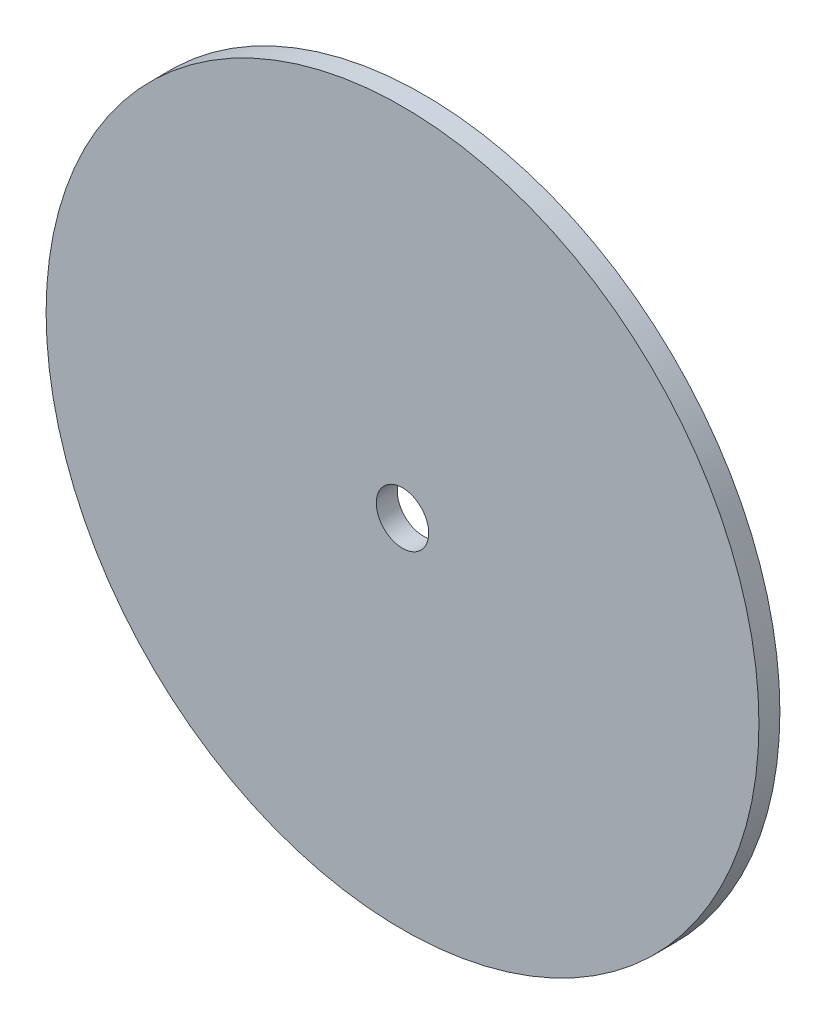
SolidWorks part; units mm, degrees
ref_plane "Front" through (0, 0, 0) normal (0, 0, 1) x (1, 0, 0)
ref_plane "Top" through (0, 0, 0) normal (0, 1, 0) x (1, 0, 0)
ref_plane "Right" through (0, 0, 0) normal (1, 0, 0) x (0, 0, -1)
sketch "Эскиз1" plane through (0, 0, 0) normal (0, 0, 1) x (1, 0, 0)
  circle A0 centre (0, 0) radius 3.4
  dimension "D1" = 6.8
extrude "Бобышка-Вытянуть1" add sketch "Эскиз1" along normal blind 0.2
sketch "Эскиз2" plane through (0, 0, 0) normal (1, 0, 0) x (0, 0, -1)
  line L0 (-4.9825, 0) -> (3.5483, 0) construction
  line L1 (0, 1) -> (-0.0926, 1)
  line L2 (0, -3.4) -> (0, 3.4) construction
  line L3 (-0.0926, 1) -> (-0.0926, 1.1)
  line L4 (-0.0926, 1.1) -> (0, 1.1)
  line L5 (0, 1.1) -> (0, 1)
  line L6 (0, 1.25) -> (-0.0926, 1.25)
  line L7 (-0.0926, 1.25) -> (-0.0926, 1.35)
  line L8 (-0.0926, 1.35) -> (0, 1.35)
  line L9 (0, 1.35) -> (0, 1.25)
  line L10 (0, 1.5) -> (-0.0926, 1.5)
  line L11 (-0.0926, 1.5) -> (-0.0926, 1.6)
  line L12 (-0.0926, 1.6) -> (0, 1.6)
  line L13 (0, 1.6) -> (0, 1.5)
  line L14 (0, 1.75) -> (-0.0926, 1.75)
  line L15 (-0.0926, 1.75) -> (-0.0926, 1.85)
  line L16 (-0.0926, 1.85) -> (0, 1.85)
  line L17 (0, 1.85) -> (0, 1.75)
  line L18 (0, 2) -> (-0.0926, 2)
  line L19 (-0.0926, 2) -> (-0.0926, 2.1)
  line L20 (-0.0926, 2.1) -> (0, 2.1)
  line L21 (0, 2.1) -> (0, 2)
  line L22 (0, 2.25) -> (-0.0926, 2.25)
  line L23 (-0.0926, 2.25) -> (-0.0926, 2.35)
  line L24 (-0.0926, 2.35) -> (0, 2.35)
  line L25 (0, 2.35) -> (0, 2.25)
  line L26 (0, 2.5) -> (-0.0926, 2.5)
  line L27 (-0.0926, 2.5) -> (-0.0926, 2.6)
  line L28 (-0.0926, 2.6) -> (0, 2.6)
  line L29 (0, 2.6) -> (0, 2.5)
  line L30 (0, 2.75) -> (-0.0926, 2.75)
  line L31 (-0.0926, 2.75) -> (-0.0926, 2.85)
  line L32 (-0.0926, 2.85) -> (0, 2.85)
  line L33 (0, 2.85) -> (0, 2.75)
  line L34 (0, 3) -> (-0.0926, 3)
  line L35 (-0.0926, 3) -> (-0.0926, 3.1)
  line L36 (-0.0926, 3.1) -> (0, 3.1)
  line L37 (0, 3.1) -> (0, 3)
  line L38 (0, 3.25) -> (-0.0926, 3.25)
  line L39 (-0.0926, 3.25) -> (-0.0926, 3.35)
  line L40 (-0.0926, 3.35) -> (0, 3.35)
  line L41 (0, 3.35) -> (0, 3.25)
  dimension "D2" = 0.1
  dimension "D3" = 0.15
  dimension "D4" = 1
  dimension "D1" = 10
revolve "Вырез-Повернуть1" cut sketch "Эскиз2" angle 360 about L0
sketch "Эскиз3" plane through (0, 0, 0) normal (0, 0, -1) x (-1, 0, 0)
  line L0 (-3.4, 0) -> (3.35, 0) construction
  line L1 (0, 3.7394) -> (0, -3.8002) construction
  line L2 (-3.5, 2.4) -> (3.5, 2.4) construction
  line L3 (-3.5, -2.7) -> (3.5, -2.7) construction
  circle A0 centre (0, 0) radius 3.4 construction
  circle A1 centre (0, 0) radius 3.35 construction
  text T0 "  45                       15" font "Century Gothic" height 0.5
  text T1 "10" font "Century Gothic" height 0.5
  text T2 "30" font "Century Gothic" height 0.5
  point P16 (0, 2.4)
  point P17 (0, -2.7)
  dimension "D1" = 2.4
  dimension "D2" = 2.7
  dimension "D3" = 7
extrude "Бобышка-Вытянуть2" add sketch "Эскиз3" along normal blind 0.1
sketch "Эскиз4" plane through (0, 0, 0) normal (0, 0, -1) x (-1, 0, 0)
  circle A0 centre (0, 0) radius 0.25
  dimension "D1" = 0.5
extrude "Вырез-Вытянуть1" cut sketch "Эскиз4" against normal through all
